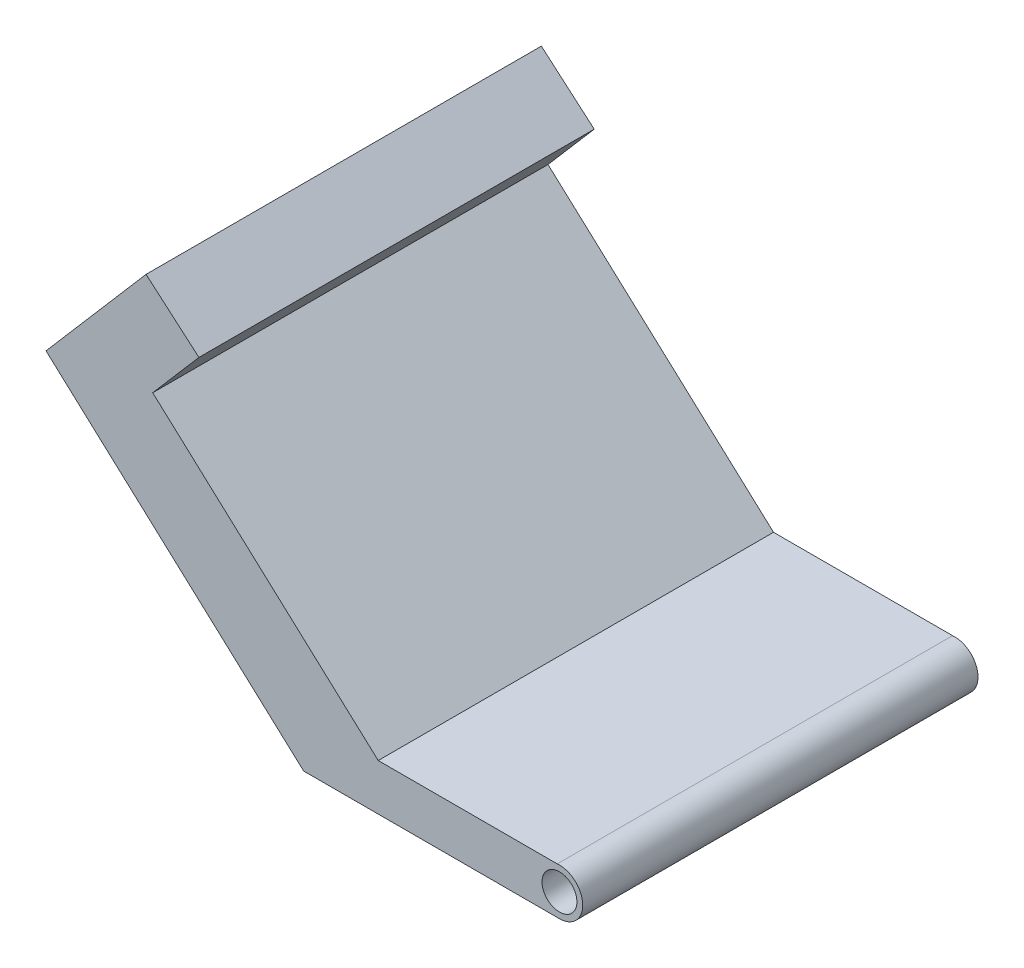
SolidWorks part; units mm, degrees
ref_plane "前视基准面" through (0, 0, 0) normal (0, 0, 1) x (1, 0, 0)
ref_plane "上视基准面" through (0, 0, 0) normal (0, 1, 0) x (1, 0, 0)
ref_plane "右视基准面" through (0, 0, 0) normal (1, 0, 0) x (0, 0, -1)
sketch "草图1" plane through (0, 0, 0) normal (0, 0, 1) x (1, 0, 0)
  line L1 (0, -10) -> (-110, -10)
  line L2 (-110, -10) -> (-220.8102, 91.0994)
  line L3 (-0.9566, 9.9541) -> (-77.9427, 9.9541)
  line L4 (-77.9427, 9.9541) -> (-174.9211, 98.4339)
  line L5 (-220.8102, 91.0994) -> (-177.7855, 141.0994)
  line L6 (-177.7855, 141.0994) -> (-155.0455, 121.5318)
  line L7 (-155.0455, 121.5318) -> (-174.9211, 98.4339)
  arc A0 (0, -10) -> (-0.9566, 9.9541) centre (0, 0) ccw
  circle A1 centre (0, 0) radius 7.5
  dimension "D2" = 15
  dimension "D3" = 10
  dimension "D1" = 110
  dimension "D4" = 30
  dimension "D5" = 150
  dimension "D6" = 50
extrude "凸台-拉伸1" add sketch "草图1" along normal blind 170
